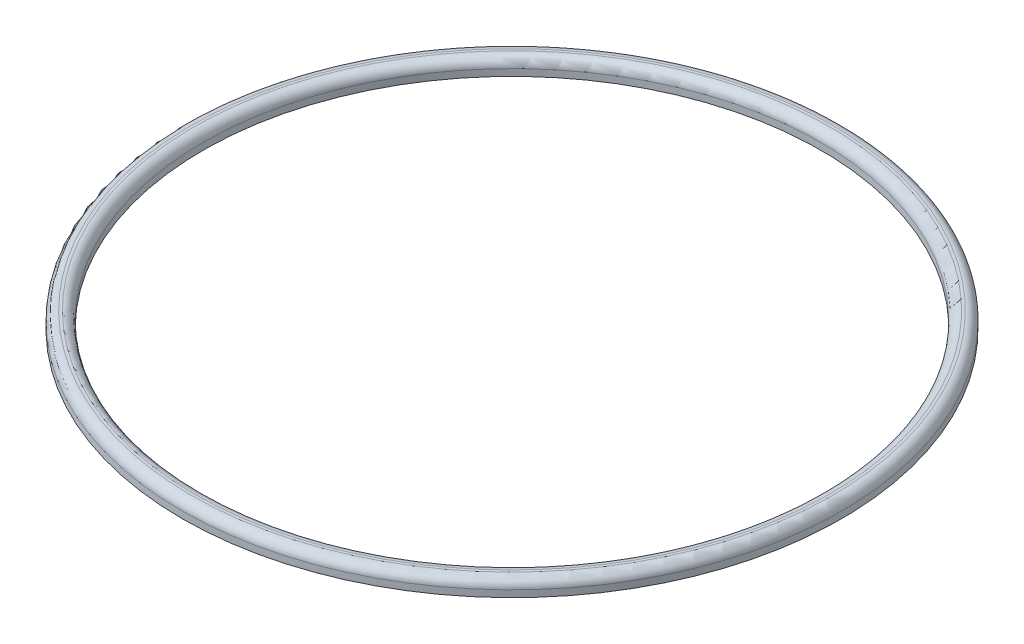
SolidWorks part; units mm, degrees
ref_plane "Front Plane" through (0, 0, 0) normal (0, 0, 1) x (1, 0, 0)
ref_plane "Top Plane" through (0, 0, 0) normal (0, 1, 0) x (1, 0, 0)
ref_plane "Right Plane" through (0, 0, 0) normal (1, 0, 0) x (0, 0, -1)
sketch "Sketch1" plane through (0, 0, 0) normal (0, 1, 0) x (1, 0, 0)
  circle A0 centre (0, 0) radius 43.875
  circle A1 centre (0, 0) radius 41.125
  dimension "D1" = 87.75
  dimension "D2" = 82.25
extrude "Boss-Extrude1" add sketch "Sketch1" along normal blind 2.1
sketch "Sketch2" plane through (0, 2.1, 0) normal (0, 1, 0) x (1, 0, 0)
  line L0 (0, 41.125) -> (0, 43.875)
  line L1 (0, -43.875) -> (0, -41.125)
  arc A0 (0, 41.125) -> (0, -41.125) centre (0, 0) cw
  circle A1 centre (0, 0) radius 41.125 construction
  arc A2 (0, 43.875) -> (0, -43.875) centre (0, 0) cw
  circle A3 centre (0, 0) radius 43.875 construction
extrude "Cut-Extrude1" [suppressed] cut sketch "Sketch2" against normal blind 0.5
fillet "Fillet1" [suppressed] radius 40
fillet "Fillet2" [suppressed] radius 10
fillet "Fillet3" radius 1.2 2 edges at (0, 2.1, 43.875) (0, 2.1, 41.125)
